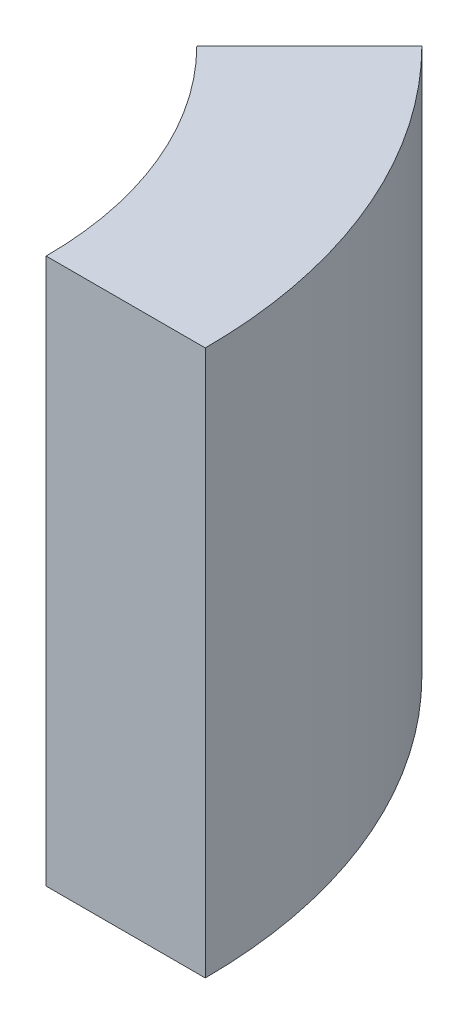
SolidWorks part; units mm, degrees
ref_plane "Front Plane" through (0, 0, 0) normal (0, 0, 1) x (1, 0, 0)
ref_plane "Top Plane" through (0, 0, 0) normal (0, 1, 0) x (1, 0, 0)
ref_plane "Right Plane" through (0, 0, 0) normal (1, 0, 0) x (0, 0, -1)
sketch "Sketch1" plane through (0, 0, 0) normal (0, 1, 0) x (1, 0, 0)
  line L0 (0, 0) -> (39.7333, 0) construction
  line L1 (11.3137, 11.3137) -> (16.2635, 16.2635)
  line L2 (16, 0) -> (23, 0)
  line L3 (14.7821, 6.1229) -> (0, 0) construction
  arc A0 (16, 0) -> (11.3137, 11.3137) centre (0, 0) ccw
  arc A1 (23, 0) -> (16.2635, 16.2635) centre (0, 0) ccw
  point P6 (14.7821, 6.1229)
  dimension "D1" = 16
  dimension "D3" = 23
  dimension "D4" = 7
  dimension "D2" = 45
  dimension "D5" = 22.5
extrude "Boss-Extrude1" add sketch "Sketch1" along normal blind 24
fillet "Fillet1" [suppressed] radius 0.4
sketch "Sketch2" plane through (0, 0, 0) normal (-0.7071, 0, -0.7071) x (-0.7071, 0, 0.7071)
  line L0 (-19.7, 5.2732) -> (-19.7, 21.6424) construction
  line L1 (-23, 24) -> (-23, 0) construction
  dimension "D1" = 3.3
sketch "Sketch3" plane through (0, 0, 0) normal (0, 0, 1) x (1, 0, 0)
  line L0 (19.7, 25.7921) -> (19.7, 3.555) construction
  line L1 (23, 24) -> (23, 0) construction
  dimension "D1" = 3.3
sketch "Sketch4" plane through (0, 0, 0) normal (0, -1, 0) x (1, 0, 0)
  line L0 (14.4414, -6.8882) -> (18.9543, -9.0407)
  line L1 (19.7955, -7.0099) -> (15.0823, -5.3409)
  line L2 (14.7821, -6.1229) -> (21.2492, -8.8017) construction
  arc A0 (11.3137, -11.3137) -> (16, 0) centre (0, 0) ccw construction
  arc A1 (18.9543, -9.0407) -> (19.7955, -7.0099) centre (0, 0) ccw
  arc A2 (16.2635, -16.2635) -> (23, 0) centre (0, 0) ccw construction
  arc A3 (15.0823, -5.3409) -> (14.4414, -6.8882) centre (0, 0) cw
  point P12 (19.4015, -8.0364)
  dimension "D1" = 2
  dimension "D2" = 6
extrude "Boss-Extrude2" add sketch "Sketch4" along normal blind 1.5
